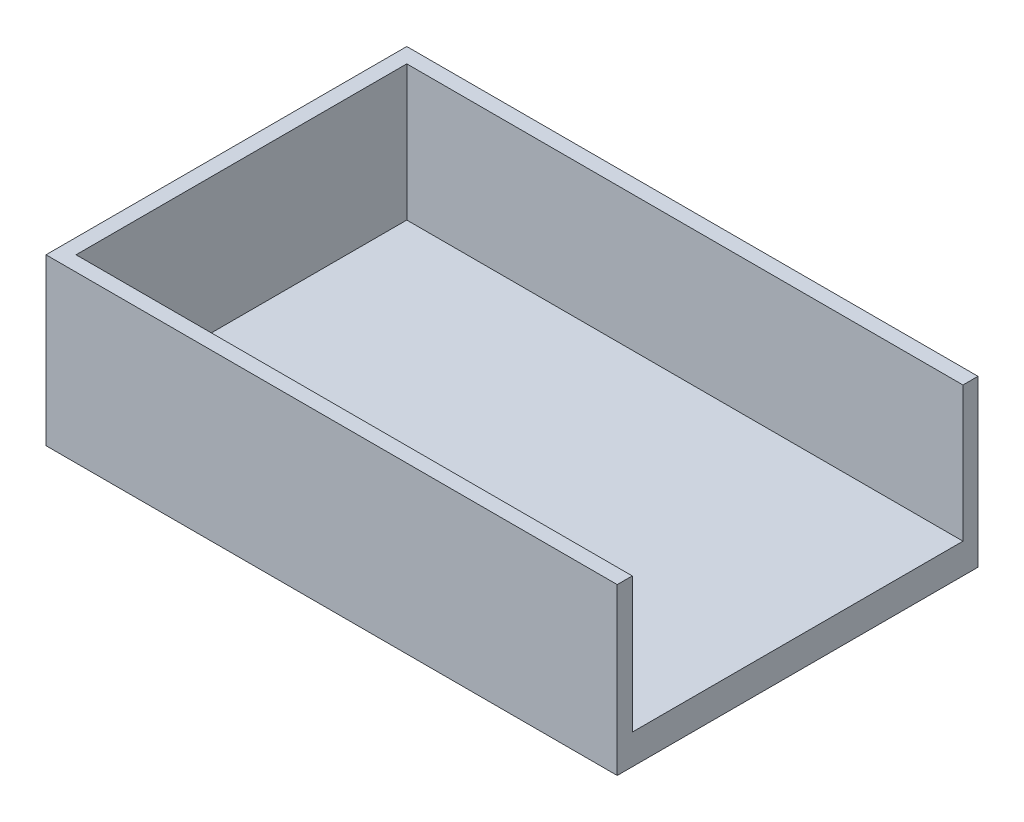
SolidWorks part; units mm, degrees
ref_plane "Front Plane" through (0, 0, 0) normal (0, 0, 1) x (1, 0, 0)
ref_plane "Top Plane" through (0, 0, 0) normal (0, 1, 0) x (1, 0, 0)
ref_plane "Right Plane" through (0, 0, 0) normal (1, 0, 0) x (0, 0, -1)
sketch "Sketch1" plane through (0, 0, 0) normal (0, 1, 0) x (1, 0, 0)
  line L1 (0, 0) -> (40, 0)
  line L2 (0, 0) -> (0, 24)
  line L3 (0, 24) -> (40, 24)
  line L4 (40, 0) -> (40, 24)
  dimension "D1" = 40
  dimension "D2" = 24
extrude "Boss-Extrude1" add sketch "Sketch1" along normal blind 2
sketch "Sketch2" plane through (0, 2, 0) normal (0, 1, 0) x (1, 0, 0)
  line L1 (3, 1) -> (39, 1)
  line L2 (3, 1) -> (3, 23)
  line L3 (3, 23) -> (39, 23)
  line L4 (39, 1) -> (39, 23)
  line L5 (0, 24) -> (40, 24)
  line L6 (0, 24) -> (0, 0)
  line L7 (0, 0) -> (40, 0)
  line L8 (40, 24) -> (40, 0)
  dimension "D1" = 22
  dimension "D2" = 36
  dimension "D3" = 1
  dimension "D4" = 1
extrude "Boss-Extrude3" add sketch "Sketch2" along normal blind 9
sketch "Sketch5" plane through (0, 2, 0) normal (0, 1, 0) x (1, 0, 0)
  line L0 (3, 1) -> (39, 1) construction
  line L1 (4, 1) -> (8, 1)
  line L2 (4, 1) -> (4, 4)
  line L3 (4, 4) -> (8, 4)
  line L4 (8, 1) -> (8, 4)
  line L6 (3, 23) -> (3, 1) construction
  dimension "D1" = 1
  dimension "D2" = 4
  dimension "D3" = 3
extrude "Cut-Extrude1" cut sketch "Sketch5" against normal blind 2
sketch "Sketch6" plane through (40, 0, 0) normal (1, 0, 0) x (0, 0, -1)
  line L1 (0, 11) -> (24, 11)
  line L2 (0, 11) -> (0, 0)
  line L3 (0, 0) -> (24, 0)
  line L4 (24, 11) -> (24, 0)
extrude "Cut-Extrude2" cut sketch "Sketch6" against normal blind 2
sketch "Sketch7" plane through (3, 0, 0) normal (1, 0, 0) x (0, 0, -1)
  line L1 (1, 2) -> (23, 2)
  line L2 (1, 2) -> (1, 11)
  line L3 (1, 11) -> (23, 11)
  line L4 (23, 2) -> (23, 11)
extrude "Cut-Extrude3" cut sketch "Sketch7" against normal blind 2
sketch "Sketch8" plane through (0, 2, 0) normal (0, 1, 0) x (1, 0, 0)
  line L0 (1, 1) -> (4, 1) construction
  line L1 (4, 4) -> (3, 4)
  line L2 (4, 4) -> (4, 1)
  line L3 (4, 1) -> (3, 1)
  line L4 (3, 4) -> (3, 1)
  dimension "D1" = 1
extrude "Cut-Extrude4" cut sketch "Sketch8" against normal blind 2
